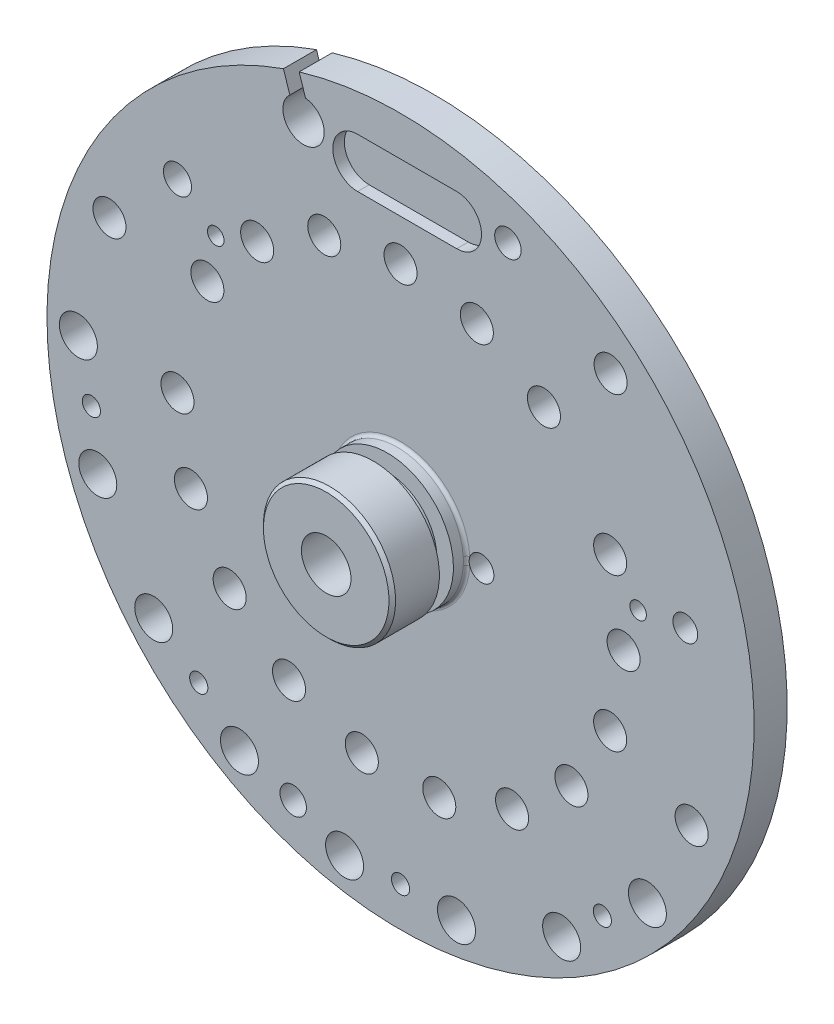
SolidWorks part; units mm, degrees
ref_plane "Front Plane" through (0, 0, 0) normal (0, 0, 1) x (1, 0, 0)
ref_plane "Top Plane" through (0, 0, 0) normal (0, 1, 0) x (1, 0, 0)
ref_plane "Right Plane" through (0, 0, 0) normal (1, 0, 0) x (0, 0, -1)
sketch "Sketch1" plane through (0, 0, 0) normal (0, 0, 1) x (1, 0, 0)
  circle A0 centre (0, 0) radius 21.4
  dimension "D1" = 42.8
extrude "Boss-Extrude1" add sketch "Sketch1" against normal blind 2
sketch "Sketch2" plane through (0, 0, -2) normal (0, 0, -1) x (-1, 0, 0)
  circle A0 centre (0, 0) radius 6.5
  dimension "D1" = 13
extrude "Boss-Extrude2" add sketch "Sketch2" along normal blind 4.7
sketch "Sketch3" plane through (0, 0, 0) normal (0, 0, 1) x (1, 0, 0)
  circle A0 centre (0, 0) radius 4
  dimension "D1" = 8
extrude "Boss-Extrude3" add sketch "Sketch3" along normal offset from surface (4.5 mm away) 6.5 up to face at (6.5, 0, -2)
sketch "Sketch5" plane through (0, 0, -6.7) normal (0, 0, -1) x (-1, 0, 0)
  circle A0 centre (0, 0) radius 3.25
  dimension "D1" = 6.5
extrude "Cut-Extrude2" cut sketch "Sketch5" against normal blind 5.2
sketch "Sketch4" plane through (0, 0, 4.5) normal (0, 0, 1) x (1, 0, 0)
  circle A0 centre (0, 0) radius 1.5
  dimension "D1" = 3
extrude "Cut-Extrude1" cut sketch "Sketch4" against normal up to next
sketch "Sketch6" plane through (0, 0, 0) normal (1, 0, 0) x (0, 0, -1)
  line L0 (-4.5, 0) -> (6.7, 0) construction
  line L1 (-4.5, 4) -> (-4.5, -4) construction
  line L2 (6.7, -6.5) -> (6.7, 6.5) construction
  line L3 (0, 4) -> (-4.5, 4) construction
  line L4 (-1.65, 4) -> (-0.8, 4)
  line L5 (-1.65, 4) -> (-1.65, 3)
  line L6 (-1.65, 3) -> (-0.8, 3)
  line L7 (-0.8, 4) -> (-0.8, 3)
  line L8 (2, -21.4) -> (2, 21.4) construction
  dimension "D1" = 2.8
  dimension "D2" = 0.85
  dimension "D3" = 6
revolve "Cut-Revolve1" cut sketch "Sketch6" angle 360 about L0
sketch "Sketch7" plane through (0, 0, 0) normal (1, 0, 0) x (0, 0, -1)
  line L0 (0, 0) -> (8.4065, 0) construction
  line L1 (6.7, -6.5) -> (6.7, 6.5) construction
  line L2 (6.7, 2.75) -> (6.2, 2.75)
  line L3 (6.7, 2.75) -> (6.7, -2.75)
  line L4 (6.7, -2.75) -> (6.2, -2.75)
  line L5 (6.2, 2.75) -> (6.2, -2.75)
  line L6 (2, -21.4) -> (2, 21.4) construction
  dimension "D1" = 4.2
  dimension "D2" = 5.5
extrude "Cut-Extrude3" cut sketch "Sketch7" against normal through all both and the other way through all
sketch "Sketch8" plane through (0, 0, 0) normal (0, 0, 1) x (1, 0, 0)
  line L0 (0, 0) -> (0, 21.4) construction
  line L1 (-2.6, 17.5) -> (3.4, 17.5) construction
  line L2 (-2.6, 19) -> (3.4, 19)
  line L3 (-2.6, 16) -> (3.4, 16)
  circle A0 centre (0, 0) radius 21.4 construction
  arc A1 (-2.6, 19) -> (-2.6, 16) centre (-2.6, 17.5) ccw
  arc A2 (3.4, 16) -> (3.4, 19) centre (3.4, 17.5) ccw
  circle A3 centre (0, 0) radius 4 construction
  point P7 (0.4, 17.5)
  dimension "D3" = 3
  dimension "D4" = 16
  dimension "D2" = 9
  dimension "D1" = 4.1
extrude "Cut-Extrude4" cut sketch "Sketch8" against normal blind 0.7
hole_wizard "Ø2.0 (2) Diameter Hole6" positions "Sketch14" profile "Sketch13" hole size "Ø2.0" standard "DIN" end condition through all
sketch "Sketch14" plane through (0, 0, -2) normal (0, 0, 1) x (1, 0, 0)
  line L7 (0, 0) -> (-21.4, 0) construction
  line L8 (0, 0) -> (-11.6913, 6.75) construction
  line L9 (-8.6776, 10.3416) -> (0, 0) construction
  line L10 (0, 0) -> (-4.6173, 12.6859) construction
  line L11 (4.6173, 12.6859) -> (0, 0) construction
  line L12 (8.6776, 10.3416) -> (0, 0) construction
  line L13 (0, 0) -> (-12.6859, -4.6173) construction
  line L14 (0, 0) -> (-10.3416, -8.6776) construction
  line L15 (-6.75, -11.6913) -> (0, 0) construction
  line L16 (0, 0) -> (-2.3443, -13.2949) construction
  line L17 (0, 0) -> (2.3443, -13.2949) construction
  line L18 (6.75, -11.6913) -> (0, 0) construction
  line L19 (10.3416, -8.6776) -> (0, 0) construction
  line L20 (12.6859, -4.6173) -> (0, 0) construction
  line L21 (0, 0) -> (13.5, 0) construction
  line L22 (12.6859, 4.6173) -> (0, 0) construction
  circle A1 centre (0, 0) radius 13.5 construction
  circle A2 centre (0, 0) radius 21.4 construction
  point P82 (-11.6913, 6.75)
  point P84 (-8.6776, 10.3416)
  point P86 (-4.6173, 12.6859)
  point P88 (4.6173, 12.6859)
  point P100 (0, 13.5)
  point P103 (8.6776, 10.3416)
  point P108 (-12.6859, -4.6173)
  point P110 (-10.3416, -8.6776)
  point P112 (-6.75, -11.6913)
  point P126 (2.3443, -13.2949)
  point P128 (6.75, -11.6913)
  point P130 (10.3416, -8.6776)
  point P132 (12.6859, -4.6173)
  point P145 (13.5, 0)
  point P147 (12.6859, 4.6173)
  point P156 (-13.5, 0)
  point P159 (-2.3443, -13.2949)
  dimension "D1" = 27
  dimension "D2" = 30
  dimension "D4" = 70
  dimension "D5" = 110
  dimension "D6" = 130
  dimension "D8" = 40
  dimension "D9" = 60
  dimension "D3" = 50
  dimension "D7" = 20
  dimension "D10" = 80
  dimension "D11" = 100
  dimension "D12" = 120
  dimension "D13" = 20
  dimension "D14" = 20
  dimension "D15" = 20
sketch "Sketch13" plane through (-11.6913, 6.75, -2) normal (1, 0, 0) x (0, 1, 0)
  line L0 (0, 0) -> (0, 6.5)
  line L1 (0, 6.5) -> (1, 6.5)
  line L2 (1, 6.5) -> (1, 0)
  line L5 (1, 0) -> (0, 0)
  line L11 (0, -6.35) -> (0, 107.95) construction
  dimension "Thru Hole Dia." = 2
  dimension "Thru Hole Depth" = 6.5
fillet "Fillet2" radius 1 1 edges at (6.5, 0, -2)
hole_wizard "Ø2.3 (2.3) Diameter Hole1" positions "Sketch20" profile "Sketch19" hole size "Ø2.3" standard "DIN" end condition through all
sketch "Sketch20" plane through (0, 0, -2) normal (0, 0, 1) x (1, 0, 0)
  line L3 (0, 0) -> (-19.5, 0) construction
  line L4 (0, 0) -> (-18.324, -6.6694) construction
  line L5 (0, 0) -> (-14.9379, -12.5344) construction
  line L6 (0, 0) -> (-9.75, -16.8875) construction
  line L7 (0, 0) -> (-3.3861, -19.2038) construction
  line L8 (0, 0) -> (3.3861, -19.2038) construction
  line L9 (0, 0) -> (9.75, -16.8875) construction
  line L10 (0, 0) -> (14.9379, -12.5344) construction
  circle A0 centre (0, 0) radius 19.5 construction
  point P35 (-19.5, 0)
  point P60 (-18.324, -6.6694)
  point P66 (-14.9379, -12.5344)
  point P69 (-9.75, -16.8875)
  point P72 (-3.3861, -19.2038)
  point P75 (3.3861, -19.2038)
  point P78 (9.75, -16.8875)
  point P81 (14.9379, -12.5344)
  dimension "D1" = 39
  dimension "D2" = 20
  dimension "D3" = 20
  dimension "D4" = 20
  dimension "D5" = 20
  dimension "D6" = 20
  dimension "D7" = 20
  dimension "D8" = 20
sketch "Sketch19" plane through (-19.5, 0, -2) normal (1, 0, 0) x (0, 1, 0)
  line L0 (0, 0) -> (0, 6.5)
  line L1 (0, 6.5) -> (1.15, 6.5)
  line L2 (1.15, 6.5) -> (1.15, 0)
  line L5 (1.15, 0) -> (0, 0)
  line L11 (0, -6.35) -> (0, 107.95) construction
  dimension "Thru Hole Dia." = 2.3
  dimension "Thru Hole Depth" = 6.5
hole_wizard "Ø2.0 (2) Diameter Hole8" positions "Sketch23" profile "Sketch21" hole size "Ø2.0" standard "DIN" end condition through all
sketch "Sketch23" plane through (0, 0, -2) normal (0, 0, 1) x (1, 0, 0)
  line L0 (0, 0) -> (-21.4, 0) construction
  line L1 (0, 0) -> (-17.6165, 7.1175) construction
  line L2 (12.7135, 14.1198) -> (0, 0) construction
  line L3 (0, 0) -> (17.6165, -7.1175) construction
  circle A0 centre (0, 0) radius 19 construction
  circle A1 centre (0, 0) radius 21.4 construction
  point P11 (-17.6165, 7.1175)
  point P15 (12.7135, 14.1198)
  point P17 (17.6165, -7.1175)
  dimension "D1" = 22
  dimension "D4" = 38
  dimension "D2" = 132
  dimension "D3" = 202
sketch "Sketch21" plane through (-17.6165, 7.1175, -2) normal (1, 0, 0) x (0, 1, 0)
  line L0 (0, 0) -> (0, 6.5)
  line L1 (0, 6.5) -> (1, 6.5)
  line L2 (1, 6.5) -> (1, 0)
  line L5 (1, 0) -> (0, 0)
  line L11 (0, -6.35) -> (0, 107.95) construction
  dimension "Thru Hole Dia." = 2
  dimension "Thru Hole Depth" = 6.5
hole_wizard "Ø2.5 (2.5) Diameter Hole1" positions "Sketch25" profile "Sketch24" hole size "Ø2.5" standard "DIN" end condition through all
sketch "Sketch25" plane through (0, 0, -2) normal (0, 0, 1) x (1, 0, 0)
  line L0 (0, 0) -> (-21.4, 0) construction
  line L1 (-5.8713, 18.0701) -> (0, 0) construction
  line L2 (0, 0) -> (-17.6165, 7.1175) construction
  circle A0 centre (0, 0) radius 19 construction
  circle A1 centre (0, 0) radius 21.4 construction
  point P4 (-5.8713, 18.0701)
  dimension "D1" = 72
sketch "Sketch24" plane through (-5.8713, 18.0701, -2) normal (1, 0, 0) x (0, 1, 0)
  line L0 (0, 0) -> (0, 6.5)
  line L1 (0, 6.5) -> (1.25, 6.5)
  line L2 (1.25, 6.5) -> (1.25, 0)
  line L5 (1.25, 0) -> (0, 0)
  line L11 (0, -6.35) -> (0, 107.95) construction
  dimension "Thru Hole Dia." = 2.5
  dimension "Thru Hole Depth" = 6.5
hole_wizard "Ø1.0 (1) Diameter Hole1" positions "Sketch27" profile "Sketch26" hole size "Ø1.0" standard "DIN" end condition through all
sketch "Sketch27" plane through (0, 0, -2) normal (0, 0, 1) x (1, 0, 0)
  line L0 (0, 0) -> (-21.4, 0) construction
  line L1 (0, 0) -> (14.3782, 2.5353) construction
  line L2 (0, 0) -> (-11.1842, 9.3847) construction
  circle A1 centre (0, 0) radius 14.6 construction
  circle A2 centre (0, 0) radius 21.4 construction
  point P26 (14.3782, 2.5353)
  point P33 (-11.1842, 9.3847)
  dimension "D3" = 29.2
  dimension "D1" = 40
  dimension "D4" = 10
sketch "Sketch26" plane through (14.3782, 2.5353, -2) normal (1, 0, 0) x (0, 1, 0)
  line L0 (0, 0) -> (0, 6.5)
  line L1 (0, 6.5) -> (0.5, 6.5)
  line L2 (0.5, 6.5) -> (0.5, 0)
  line L5 (0.5, 0) -> (0, 0)
  line L11 (0, -6.35) -> (0, 107.95) construction
  dimension "Thru Hole Dia." = 1
  dimension "Thru Hole Depth" = 6.5
hole_wizard "Ø1.7 (1.7) Diameter Hole2" positions "Sketch43" profile "Sketch42" hole size "Ø1.7" standard "DIN" end condition through all
sketch "Sketch43" plane through (0, 0, -2) normal (0, 0, -1) x (-1, 0, 0)
  point P0 (13.5, 11.2)
  point P8 (0, 0)
  dimension "D1" = 13.5
  dimension "D2" = 11.2
sketch "Sketch42" plane through (-13.5, 11.2, -2) normal (1, 0, 0) x (0, 1, 0)
  line L0 (0, 0) -> (0, 6.5)
  line L1 (0, 6.5) -> (0.85, 6.5)
  line L2 (0.85, 6.5) -> (0.85, 0)
  line L5 (0.85, 0) -> (0, 0)
  line L11 (0, -6.35) -> (0, 107.95) construction
  dimension "Thru Hole Dia." = 1.7
  dimension "Thru Hole Depth" = 6.5
hole_wizard "M1.4x0.3 Tapped Hole1" positions "Sketch31" profile "Sketch33" tap size "M1.4x0.3" standard "ANSI Metric" end condition through all
sketch "Sketch31" plane through (0, 0, -2) normal (0, 0, 1) x (1, 0, 0)
  line L0 (0, 0) -> (-18.7113, -3.2993) construction
  line L1 (0, 0) -> (-21.4, 0) construction
  line L2 (0, 0) -> (12.213, -14.5548) construction
  line L3 (0, 0) -> (0, -19) construction
  line L4 (0, 0) -> (-12.213, -14.5548) construction
  circle A0 centre (0, 0) radius 19 construction
  circle A2 centre (0, 0) radius 21.4 construction
  point P22 (-18.7113, -3.2993)
  point P24 (12.213, -14.5548)
  point P26 (-12.213, -14.5548)
  point P28 (0, -19)
  dimension "D1" = 38
  dimension "D2" = 10
  dimension "D3" = 40
  dimension "D4" = 40
sketch "Sketch33" plane through (-18.7113, -3.2993, -2) normal (1, 0, 0) x (0, 1, 0)
  line L0 (0, 0) -> (0, 6.5)
  line L1 (0, 6.5) -> (0.55, 6.5)
  line L2 (0.55, 6.5) -> (0.55, 0)
  line L5 (0.55, 0) -> (0, 0)
  line L11 (0, -6.35) -> (0, 107.95) construction
  dimension "Thru Tap Drill Dia." = 1.1
  dimension "Thru Tap Drill Depth" = 6.5
cosmetic thread "Hole Thread6" parameters "D2"=1.4
cosmetic thread "Hole Thread7" parameters "D2"=1.4
cosmetic thread "Hole Thread8" parameters "D2"=1.4
cosmetic thread "Hole Thread9" parameters "D2"=1.4
hole_wizard "M2 Tapped Hole1" positions "Sketch35" profile "Sketch34" tap size "M2" standard "DIN" end condition through all
sketch "Sketch35" plane through (0, 0, 0) normal (0, 0, 1) x (1, 0, 0)
  line L0 (0, 0) -> (-6.4984, -17.8542) construction
  line L1 (0, 0) -> (0, -21.4) construction
  line L2 (0, 0) -> (0, 21.4) construction
  line L3 (6.4984, 17.8542) -> (0, 0) construction
  circle A0 centre (0, 0) radius 19 construction
  circle A1 centre (0, 0) radius 21.4 construction
  point P28 (6.4984, 17.8542)
  point P30 (-6.4984, -17.8542)
  dimension "D1" = 38
  dimension "D2" = 20
  dimension "D3" = 20
sketch "Sketch34" plane through (6.4984, 17.8542, 0) normal (1, 0, 0) x (0, -1, 0)
  line L0 (0, 0) -> (0, 6.7)
  line L1 (0, 6.7) -> (0.8, 6.7)
  line L2 (0.8, 6.7) -> (0.8, 0)
  line L5 (0.8, 0) -> (0, 0)
  line L11 (0, -6.35) -> (0, 107.95) construction
  dimension "Thru Tap Drill Dia." = 1.6
  dimension "Thru Tap Drill Depth" = 6.7
cosmetic thread "Hole Thread5" parameters "D2"=2
cosmetic thread "Hole Thread10" parameters "D2"=2
hole_wizard "CBORE for M1.7 Hex Socket Head Cap Screw1" positions "Sketch38" profile "Sketch36" counterbore size "M1.6" standard "DIN" end condition through all
sketch "Sketch38" plane through (0, 0, -2) normal (0, 0, 1) x (1, 0, 0)
  line L0 (0, 0) -> (21.4, 0) construction
  line L1 (0, 0) -> (17.2341, 3.0388) construction
  circle A0 centre (0, 0) radius 17.5 construction
  circle A1 centre (0, 0) radius 21.4 construction
  point P0 (17.2341, 3.0388)
  dimension "D1" = 35
  dimension "D2" = 10
sketch "Sketch36" plane through (17.2341, 3.0388, -2) normal (1, 0, 0) x (0, 1, 0)
  line L0 (0, 0) -> (0, 6.5)
  line L1 (0, 6.5) -> (0.75, 6.5)
  line L3 (0.75, 6.5) -> (0.75, 0.5)
  line L4 (0.75, 0.5) -> (0.9, 0.5)
  line L5 (0.9, 0.5) -> (0.9, 0)
  line L7 (0.9, 0) -> (0, 0)
  line L11 (0, -6.35) -> (0, 107.95) construction
  dimension "Thru Hole Dia." = 1.5
  dimension "Thru Hole Depth" = 6.5
  dimension "C'Bore Dia." = 1.8
  dimension "C'Bore Depth" = 0.5
cosmetic thread "Cosmetic Thread1" parameters "D2"=1.7
hole_wizard "CBORE for M1.7 Hex Socket Head Cap Screw2" positions "Sketch40" profile "Sketch39" counterbore size "M1.6" standard "DIN" end condition through all
sketch "Sketch40" plane through (0, 0, -6.2) normal (0, 0, -1) x (-1, 0, 0)
  point P0 (-4.9, 0)
  dimension "D1" = 4.9
sketch "Sketch39" plane through (4.9, 0, -6.2) normal (1, 0, 0) x (0, 1, 0)
  line L0 (0, 0) -> (0, 10.7)
  line L1 (0, 10.7) -> (0.75, 10.7)
  line L3 (0.75, 10.7) -> (0.75, 1.2)
  line L4 (0.75, 1.2) -> (0.9, 1.2)
  line L5 (0.9, 1.2) -> (0.9, 0)
  line L7 (0.9, 0) -> (0, 0)
  line L11 (0, -6.35) -> (0, 107.95) construction
  dimension "Thru Hole Dia." = 1.5
  dimension "Thru Hole Depth" = 10.7
  dimension "C'Bore Dia." = 1.8
  dimension "C'Bore Depth" = 1.2
cosmetic thread "Cosmetic Thread2" parameters "D1"=4.3, "D2"=1.7
sketch "Sketch41" plane through (0, 0, -2) normal (0, 0, 1) x (1, 0, 0)
  line L0 (0, 0) -> (-5.8713, 18.0701) construction
  line L1 (-5.7498, 19.3142) -> (-6.1356, 20.5016)
  line L2 (-6.7009, 19.0051) -> (-7.0867, 20.1925)
  line L3 (-0.4755, -0.1545) -> (-6.3469, 17.9156) construction
  line L4 (0.4755, 0.1545) -> (-5.3958, 18.2246) construction
  circle A0 centre (0, 0) radius 21.4 construction
  arc A1 (-6.1356, 20.5016) -> (-7.0867, 20.1925) centre (0, 0) ccw
  circle A2 centre (-5.8713, 18.0701) radius 1.25 construction
  arc A3 (-5.7498, 19.3142) -> (-6.7009, 19.0051) centre (-5.8713, 18.0701) ccw
  dimension "D1" = 0.5
  dimension "D2" = 0.5
extrude "Cut-Extrude5" cut sketch "Sketch41" along normal through all contours A1 L2 A3 L1
fillet "Fillet3" radius 0.2 1 edges at (4, 0, 0)
chamfer "Chamfer1" distance 0.2 angle 45 1 edges at (4, 0, 4.5)
